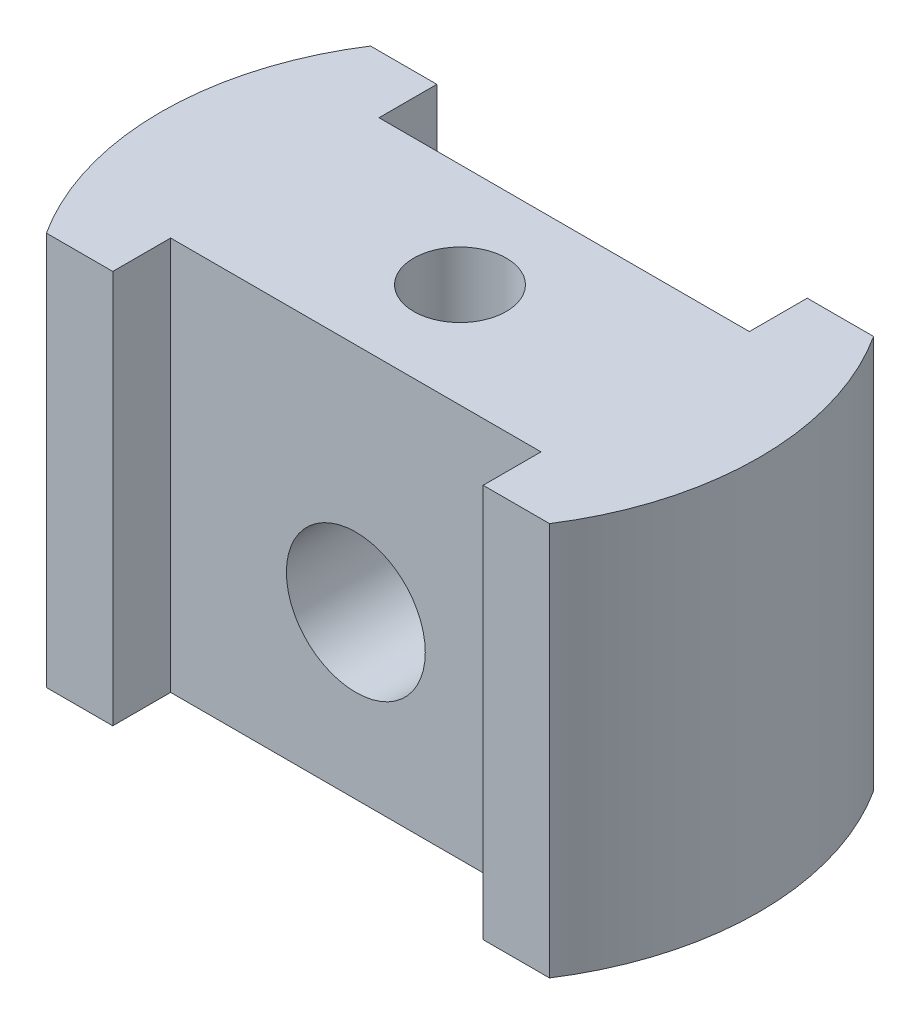
SolidWorks part; units mm, degrees
ref_plane "Front Plane" through (0, 0, 0) normal (0, 0, 1) x (1, 0, 0)
ref_plane "Top Plane" through (0, 0, 0) normal (0, 1, 0) x (1, 0, 0)
ref_plane "Right Plane" through (0, 0, 0) normal (1, 0, 0) x (0, 0, -1)
sketch "Sketch1" plane through (0, 0, 0) normal (0, 1, 0) x (1, 0, 0)
  line L0 (-8, 7) -> (-8, 4.5)
  line L1 (-8, 4.5) -> (8, 4.5)
  line L2 (8, 4.5) -> (8, 7)
  line L3 (8, 7) -> (10.8666, 7)
  line L4 (-8, 7) -> (-10.8666, 7)
  line L6 (-8, -7) -> (-10.8666, -7)
  line L7 (8, -7) -> (10.8666, -7)
  line L8 (8, -4.5) -> (8, -7)
  line L9 (-8, -4.5) -> (8, -4.5)
  line L10 (-8, -7) -> (-8, -4.5)
  arc A0 (-10.8666, 7) -> (-10.8666, -7) centre (0, 0) ccw
  arc A1 (10.8666, -7) -> (10.8666, 7) centre (0, 0) ccw
  point P5 (0, 4.5)
  dimension "D2" = 8
  dimension "D1" = 12.926
  dimension "D3" = 10.8666
  dimension "D4" = 4.5
extrude "Boss-Extrude1" add sketch "Sketch1" along normal mid plane 17
hole_wizard "Tap Drill for M4x0.7 Tap1" positions "Sketch3" profile "Sketch4" hole size "M4x0.7" standard "ANSI Metric"
sketch "Sketch3" plane through (0, 8.5, 0) normal (0, 1, 0) x (1, 0, 0)
  point P0 (0, 0)
sketch "Sketch4" plane through (0, 8.5, 0) normal (1, 0, 0) x (0, 0, 1)
  line L0 (0, 0) -> (0, 6.5)
  line L1 (0, 6.5) -> (2, 5.2983)
  line L2 (2, 5.2983) -> (2, 0)
  line L5 (2, 0) -> (0, 0)
  line L10 (0, 6.5) -> (-2, 5.2983) construction
  line L11 (0, -6.35) -> (0, 107.95) construction
  dimension "Hole Dia." = 4
  dimension "Hole Depth" = 6.5
  dimension "Drill Angle" = 118
sketch "Sketch5" plane through (0, 0, 0) normal (0, 0, 1) x (1, 0, 0)
  circle A0 centre (0, -1.5) radius 3
  dimension "D1" = 6
  dimension "D2" = 1.5
extrude "Cut-Extrude1" cut sketch "Sketch5" against normal through all both and the other way through all
